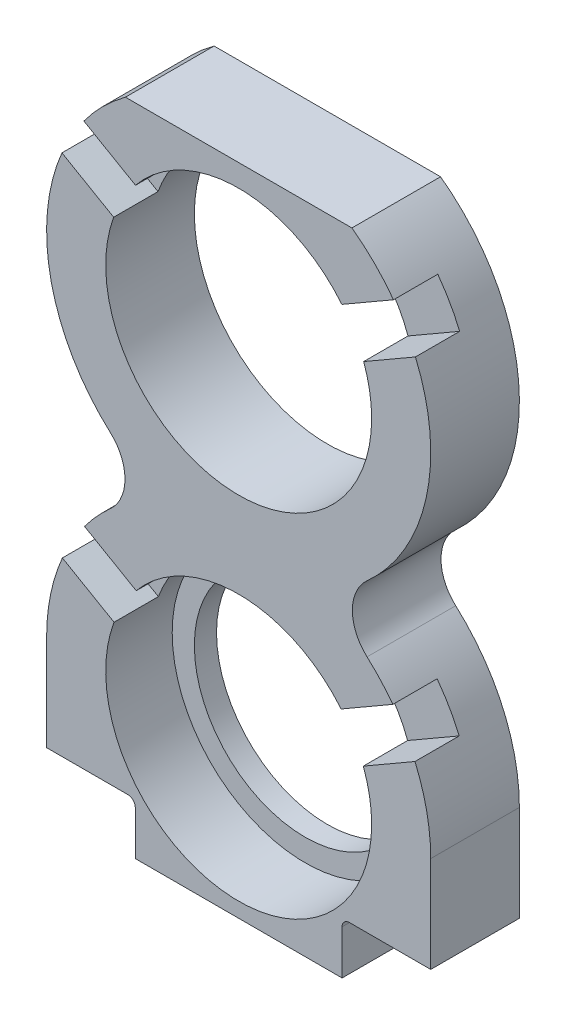
SolidWorks part; units mm, degrees
material "7075-O (SS)"
ref_plane "前视基准面" through (0, 0, 0) normal (0, 0, 1) x (1, 0, 0)
ref_plane "上视基准面" through (0, 0, 0) normal (0, 1, 0) x (1, 0, 0)
ref_plane "右视基准面" through (0, 0, 0) normal (1, 0, 0) x (0, 0, -1)
sketch "草图1" plane through (0, 0, 0) normal (0, 0, 1) x (1, 0, 0)
  line L1 (0, 0) -> (26, 0)
  line L2 (0, 0) -> (0, 46.8)
  line L3 (0, 46.8) -> (26, 46.8)
  line L4 (26, 0) -> (26, 46.8)
  dimension "D1" = 26
  dimension "D2" = 46.8
extrude "凸台-拉伸1" add sketch "草图1" along normal blind 6
sketch "草图2" plane through (0, 0, 6) normal (0, 0, 1) x (1, 0, 0)
  line L0 (0, 46.8) -> (0, 0) construction
  line L1 (0, 0) -> (26, 0) construction
  circle A0 centre (13, 36.3) radius 9
  circle A1 centre (13, 12.5) radius 7.5
  dimension "D1" = 18
  dimension "D3" = 12.5
  dimension "D2" = 13
  dimension "D4" = 23.8
extrude "切除-拉伸1" cut sketch "草图2" against normal through all
sketch "草图3" plane through (0, 0, 6) normal (0, 0, 1) x (1, 0, 0)
  line L0 (26, 0) -> (26, 46.8) construction
  line L1 (0, 0) -> (26, 0)
  line L2 (0, 0) -> (0, 2.5)
  line L3 (0, 2.5) -> (26, 2.5)
  line L4 (26, 0) -> (26, 2.5)
  dimension "D1" = 2.5
extrude "切除-拉伸2" cut sketch "草图3" against normal through all
chamfer "倒角1" distance 5 angle 45 2 edges at (26, 46.8, 3) (0, 46.8, 3)
sketch "草图4" plane through (0, 2.5, 0) normal (0, -1, 0) x (1, 0, 0)
  line L0 (26, 0) -> (0, 0) construction
  line L1 (0, 6) -> (6, 6)
  line L2 (0, 6) -> (0, 0)
  line L3 (0, 0) -> (6, 0)
  line L4 (6, 6) -> (6, 0)
  line L5 (26, 0) -> (26, 6) construction
  line L6 (26, 6) -> (20, 6)
  line L7 (26, 6) -> (26, 0)
  line L8 (26, 0) -> (20, 0)
  line L9 (20, 6) -> (20, 0)
  line L10 (26, 6) -> (0, 6) construction
  dimension "D1" = 6
  dimension "D2" = 6
extrude "切除-拉伸3" cut sketch "草图4" against normal blind 3.5
sketch "草图5" plane through (0, 6, 0) normal (0, -1, 0) x (1, 0, 0)
  line L0 (13, 0) -> (13, 6) construction
  line L1 (0, 0) -> (6, 0) construction
  circle A0 centre (3, 3) radius 1.6
  circle A1 centre (23, 3) radius 1.6
  dimension "D1" = 3.2
  dimension "D2" = 3.2
  dimension "D3" = 20
  dimension "D4" = 10
  dimension "D5" = 3
extrude "切除-拉伸4" cut sketch "草图5" against normal blind 3
fillet "圆角1" radius 0.5 2 edges at (6, 6, 3) (20, 6, 3)
sketch "草图6" plane through (0, 0, 6) normal (0, 0, 1) x (1, 0, 0)
  line L0 (26, 6) -> (26, 41.8) construction
  line L1 (0, 12.5) -> (0, 6)
  line L2 (0, 6) -> (0, 0)
  line L4 (26, 12.5) -> (26, 6)
  line L5 (0, 0) -> (26, 0)
  line L7 (26, 0) -> (26, 6)
  arc A0 (7.7665, 24.4) -> (0, 12.5) centre (13, 12.5) ccw
  arc A1 (18.2335, 24.4) -> (7.7665, 24.4) centre (13, 36.3) ccw
  arc A2 (26, 12.5) -> (18.2335, 24.4) centre (13, 12.5) ccw
extrude "切除-拉伸5" cut sketch "草图6" against normal through all flip side to cut
fillet "圆角2" radius 3 2 edges at (7.7665, 24.4, 3) (18.2335, 24.4, 3)
ref_plane "基准面1" through (13, 0, 0) normal (1, 0, 0) x (0, 0, -1)
sketch "草图7" plane through (0, 0, 6) normal (0, 0, 1) x (1, 0, 0)
  circle A0 centre (13, 12.5) radius 9
extrude "切除-拉伸6" cut sketch "草图7" against normal blind 4.5
sketch "草图8" plane through (0, 0, 6) normal (0, 0, 1) x (1, 0, 0)
  line L1 (13, 36.2128) -> (5.9091, 40.3067) construction
  line L2 (13, -3.3) -> (13, 3.3) construction
  line L3 (13, 12.5) -> (8.5917, 15.0451) construction
  line L4 (5.1591, 39.0077) -> (6.6591, 41.6058)
  line L5 (7.8417, 13.7461) -> (9.3417, 16.3441)
  line L6 (5.1591, 39.0077) -> (-0.4923, 42.2706)
  line L7 (-0.4923, 42.2706) -> (1.0077, 44.8686)
  line L8 (1.0077, 44.8686) -> (6.6591, 41.6058)
  line L10 (7.8417, 13.7461) -> (0, 18.2735)
  line L11 (0, 18.2735) -> (1.5, 20.8716)
  line L12 (1.5, 20.8716) -> (9.3417, 16.3441)
  line L13 (13, 36.2128) -> (13, 12.5) construction
  line L14 (24.5, 20.8716) -> (16.6583, 16.3441)
  line L15 (26, 18.2735) -> (24.5, 20.8716)
  line L16 (18.1583, 13.7461) -> (26, 18.2735)
  line L17 (24.9923, 44.8686) -> (19.3409, 41.6058)
  line L18 (26.4923, 42.2706) -> (24.9923, 44.8686)
  line L19 (20.8409, 39.0077) -> (26.4923, 42.2706)
  line L20 (18.1583, 13.7461) -> (16.6583, 16.3441)
  line L21 (20.8409, 39.0077) -> (19.3409, 41.6058)
  point P8 (5.9091, 40.3067)
  point P13 (8.5917, 15.0451)
  dimension "D1" = 60
  dimension "D2" = 60
  dimension "D3" = 3
  dimension "D4" = 3
extrude "切除-拉伸7" cut sketch "草图8" against normal blind 3
